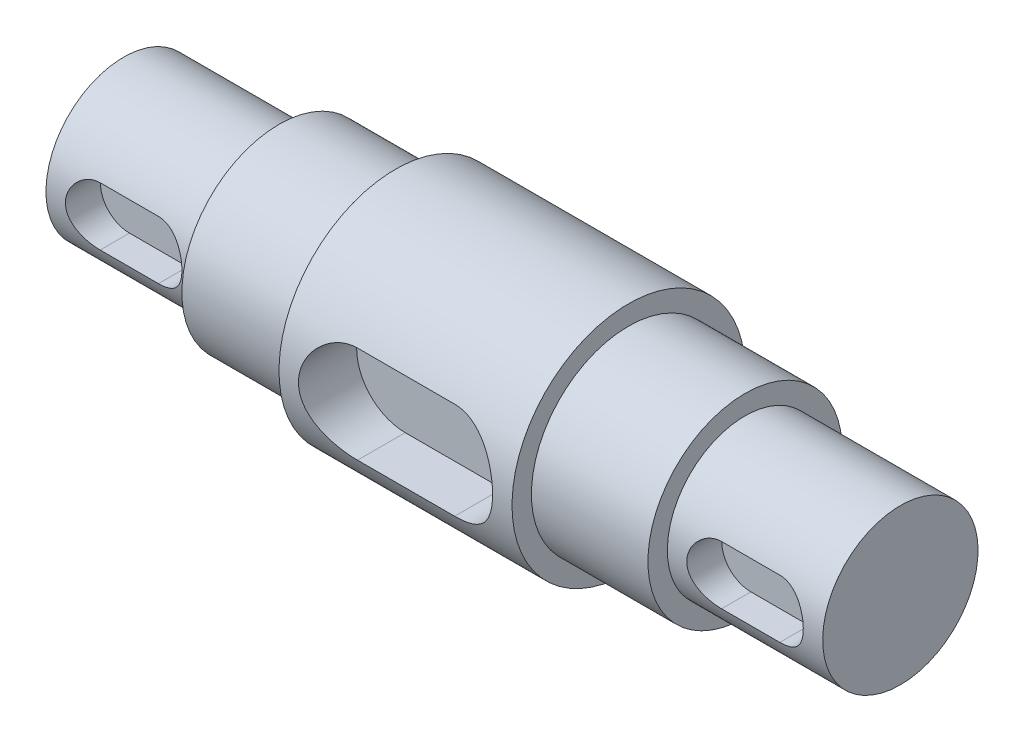
SolidWorks part; units mm, degrees
ref_plane "前视基准面" through (0, 0, 0) normal (0, 0, 1) x (1, 0, 0)
ref_plane "上视基准面" through (0, 0, 0) normal (0, 1, 0) x (1, 0, 0)
ref_plane "右视基准面" through (0, 0, 0) normal (1, 0, 0) x (0, 0, -1)
other "Configuration Table"
sketch "草图1" plane through (0, 0, 0) normal (0, 0, 1) x (1, 0, 0)
  line L0 (0, 0) -> (0, 4)
  line L1 (0, 4) -> (8, 4)
  line L2 (8, 4) -> (8, 5)
  line L3 (8, 5) -> (14, 5)
  line L4 (14, 5) -> (14, 6)
  line L5 (14, 6) -> (26, 6)
  line L6 (20, 6) -> (20, -36.3037) construction
  line L7 (26, 5) -> (26, 6)
  line L8 (32, 5) -> (26, 5)
  line L9 (32, 4) -> (32, 5)
  line L10 (40, 4) -> (32, 4)
  line L11 (40, 0) -> (40, 4)
  line L12 (0, 0) -> (40, 0)
  dimension "D1" = 4
  dimension "D2" = 1
  dimension "D3" = 1
  dimension "D4" = 6
  dimension "D5" = 12
  dimension "D6" = 8
revolve "旋转1" add sketch "草图1" angle 360 about L12
ref_plane "基准面1" through (0, 0, 6) normal (0, 0, 1) x (1, 0, 0)
sketch "草图2" plane through (0, 0, 6) normal (0, 0, 1) x (1, 0, 0)
  line L0 (17.5, 0) -> (22.5, 0) construction
  line L1 (17.5, 2.5) -> (22.5, 2.5)
  line L2 (17.5, -2.5) -> (22.5, -2.5)
  line L3 (26, -6) -> (26, 6) construction
  arc A0 (17.5, 2.5) -> (17.5, -2.5) centre (17.5, 0) ccw
  arc A1 (22.5, -2.5) -> (22.5, 2.5) centre (22.5, 0) ccw
  point P3 (20, 0)
  point P8 (25, 0)
  dimension "D1" = 2.5
  dimension "D2" = 5
  dimension "D3" = 1
extrude "切除-拉伸1" cut sketch "草图2" against normal blind 3
ref_plane "基准面2" through (0, 0, 4) normal (0, 0, 1) x (1, 0, 0)
sketch "草图3" plane through (0, 0, 4) normal (0, 0, 1) x (1, 0, 0)
  line L0 (2.5, 0) -> (5.5, 0) construction
  line L1 (2.5, 1.5) -> (5.5, 1.5)
  line L2 (2.5, -1.5) -> (5.5, -1.5)
  line L3 (8, 4) -> (8, -4) construction
  line L4 (20, 6) -> (20, -14.7419) construction
  line L5 (26, 6) -> (14, 6) construction
  line L6 (37.5, 0) -> (34.5, 0) construction
  line L7 (37.5, 1.5) -> (34.5, 1.5)
  line L8 (37.5, -1.5) -> (34.5, -1.5)
  arc A0 (2.5, 1.5) -> (2.5, -1.5) centre (2.5, 0) ccw
  arc A1 (5.5, -1.5) -> (5.5, 1.5) centre (5.5, 0) ccw
  arc A2 (37.5, 1.5) -> (37.5, -1.5) centre (37.5, 0) cw
  arc A3 (34.5, -1.5) -> (34.5, 1.5) centre (34.5, 0) cw
  point P3 (4, 0)
  point P8 (7, 0)
  point P17 (36, 0)
  dimension "D1" = 1.5
  dimension "D2" = 3
  dimension "D3" = 1
extrude "切除-拉伸2" cut sketch "草图3" against normal blind 1.8
mirror "镜向1" about plane through (0, 0, 0) normal (0, 0, 1) of "切除-拉伸2"
